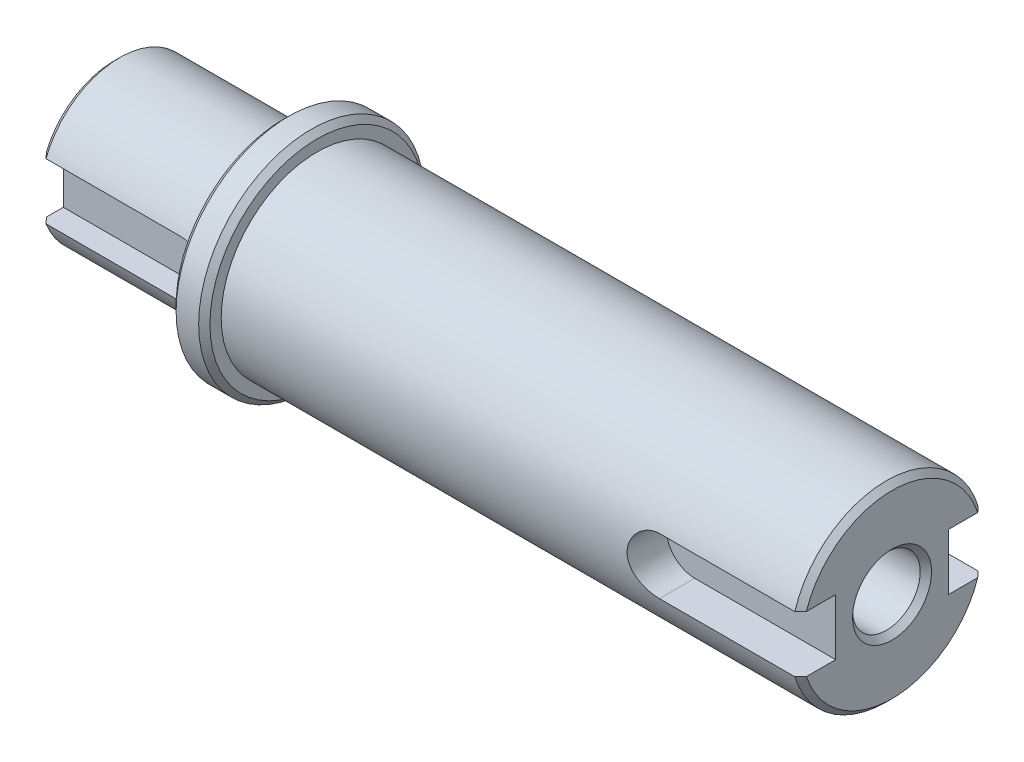
SolidWorks part; units mm, degrees
ref_plane "前视基准面" through (0, 0, 0) normal (0, 0, 1) x (1, 0, 0)
ref_plane "上视基准面" through (0, 0, 0) normal (0, 1, 0) x (1, 0, 0)
ref_plane "右视基准面" through (0, 0, 0) normal (1, 0, 0) x (0, 0, -1)
other "Configuration Table"
sketch "草图1" plane through (0, 0, 0) normal (0, 0, 1) x (1, 0, 0)
  line L0 (0, 0) -> (83.8798, 0) construction
  line L1 (0, 0) -> (0, 7)
  line L2 (0, 7) -> (15, 7)
  line L3 (15, 7) -> (15, 10)
  line L4 (15, 10) -> (18, 10)
  line L5 (18, 10) -> (18, 8.5)
  line L6 (18, 8.5) -> (69, 8.5)
  line L7 (69, 8.5) -> (69, 0)
  line L8 (69, 0) -> (0, 0)
  point P3 (83.8798, 0)
  dimension "D1" = 20
  dimension "D2" = 14
  dimension "D3" = 17
  dimension "D4" = 15
  dimension "D5" = 18
  dimension "D6" = 51
revolve "旋转1" add sketch "草图1" angle 360 about L0
chamfer "倒角1" distance 0.5 angle 45 4 edges at (69, 0, 8.5) (18, 0, 10) (15, 0, 10) (0, 0, 7)
hole_wizard "M6 螺纹孔的螺纹孔钻头1" positions "草图2" profile "草图3" hole size "M6" standard "GB"
sketch "草图2" plane through (69, 0, 0) normal (1, 0, 0) x (0, 0, -1)
  point P0 (0, 0)
sketch "草图3" plane through (69, 0, 0) normal (0, 1, 0) x (0, 0, -1)
  line L0 (0, 0) -> (0, 16.8026)
  line L1 (0, 16.8026) -> (3, 15)
  line L2 (3, 15) -> (3, 0.5)
  line L3 (3, 0.5) -> (3.5, 0)
  line L5 (3.5, 0) -> (0, 0)
  line L6 (-3, 0.5) -> (-3.5, 0) construction
  line L10 (0, 16.8026) -> (-3, 15) construction
  line L11 (0, -6.35) -> (0, 107.95) construction
  dimension "孔直径" = 6
  dimension "孔深度" = 15
  dimension "近端锥形沉头孔直径" = 7
  dimension "近端锥形沉头孔角度" = 90
  dimension "导头角度" = 118
sketch "草图4" plane through (0, 0, 0) normal (0, 0, 1) x (1, 0, 0)
  line L0 (0, 2.5) -> (12.5, 2.5)
  line L1 (0, 6.5) -> (0, -6.5) construction
  line L2 (12.5, -2.5) -> (0, -2.5)
  line L3 (0, -2.5) -> (0, 2.5)
  arc A0 (12.5, 2.5) -> (12.5, -2.5) centre (12.5, 0) cw
  point P6 (0, 0)
  point P15 (69, 2.5)
  dimension "D1" = 5
  dimension "D2" = 12.5
extrude "切除-拉伸1" cut sketch "草图4" along normal blind 10 from offset 4.5
sketch "草图5" plane through (0, 0, 0) normal (0, 0, 1) x (1, 0, 0)
  line L0 (69, 2.5) -> (56.5, 2.5)
  line L1 (69, -8) -> (69, 8) construction
  line L2 (56.5, -2.5) -> (69, -2.5)
  line L3 (69, -2.5) -> (69, 2.5)
  line L4 (68.5, 0) -> (69, 0) construction
  arc A0 (56.5, 2.5) -> (56.5, -2.5) centre (56.5, 0) ccw
  point P9 (69, 0)
  dimension "D1" = 5
  dimension "D2" = 12.5
extrude "切除-拉伸2" cut sketch "草图5" along normal blind 10 from offset 5
pattern_circular "阵列(圆周)1" count 2 over 360 about axis through (0, 0, 0) along (1, 0, 0) of "切除-拉伸2"
